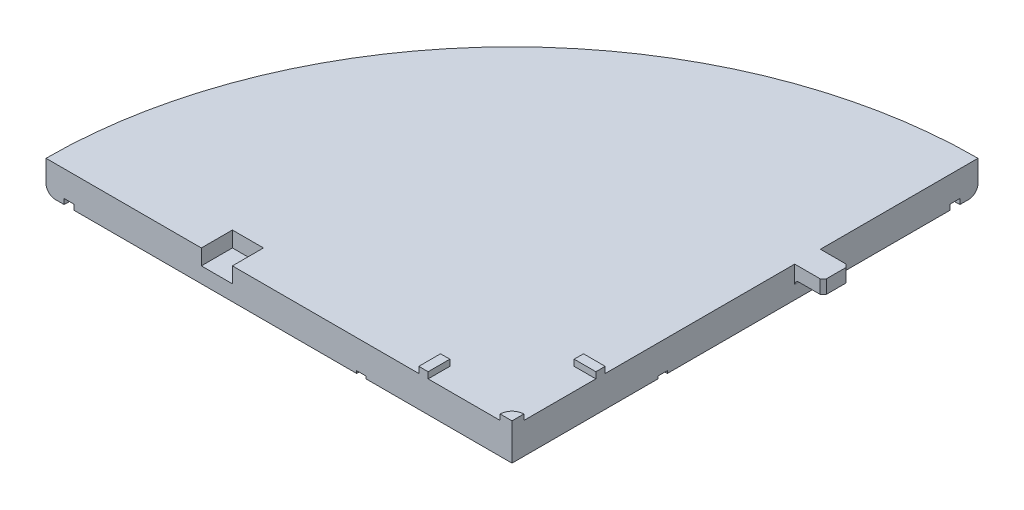
SolidWorks part; units mm, degrees
ref_plane "Front Plane" through (0, 0, 0) normal (0, 0, 1) x (1, 0, 0)
ref_plane "Top Plane" through (0, 0, 0) normal (0, 1, 0) x (1, 0, 0)
ref_plane "Right Plane" through (0, 0, 0) normal (1, 0, 0) x (0, 0, -1)
sketch "Sketch1" plane through (0, 0, 0) normal (0, 1, 0) x (1, 0, 0)
  circle A0 centre (0, 0) radius 150
extrude "Boss-Extrude3" add sketch "Sketch1" along normal blind 10
sketch "Sketch4" plane through (0, 10, 0) normal (0, 1, 0) x (1, 0, 0)
  line L0 (0, 0) -> (0, 162.3297)
  line L1 (0, 162.3297) -> (183.6782, 162.3297)
  line L2 (183.6782, 162.3297) -> (183.6782, -176.4278)
  line L3 (183.6782, -176.4278) -> (-217.9165, -176.4278)
  line L4 (-217.9165, -176.4278) -> (-217.9165, 0)
  line L5 (-217.9165, 0) -> (0, 0)
extrude "Cut-Extrude2" cut sketch "Sketch4" against normal blind 10
sketch "Sketch5" plane through (0, 10, 0) normal (0, 1, 0) x (1, 0, 0)
  line L0 (0, 3.825) -> (0, 0)
  line L1 (0, 0) -> (-3.825, 0)
  arc A0 (0, 3.825) -> (-3.825, 0) centre (0, 0) ccw
extrude "Boss-Extrude4" add sketch "Sketch5" along normal blind 1.8
sketch "Sketch6" plane through (0, 10, 0) normal (0, 1, 0) x (1, 0, 0)
  line L1 (-3.825, 0) -> (-150, 0) construction
  line L2 (-27, 0) -> (-27, 7)
  line L3 (-27, 7) -> (-30, 7)
  line L4 (-30, 7) -> (-30, 0)
  line L5 (-27, 0) -> (-30, 0)
extrude "Boss-Extrude5" add sketch "Sketch6" along normal blind 2
sketch "Sketch7" plane through (0, 10, 0) normal (0, 1, 0) x (1, 0, 0)
  line L1 (0, 150) -> (0, 3.825) construction
  line L2 (0, 27) -> (-7, 27)
  line L3 (-7, 27) -> (-7, 30)
  line L4 (-7, 30) -> (0, 30)
  line L5 (0, 30) -> (0, 27)
extrude "Boss-Extrude6" add sketch "Sketch7" along normal blind 2
sketch "Sketch8" plane through (0, 10, 0) normal (0, 1, 0) x (1, 0, 0)
  line L0 (0, 0) -> (-90, 0)
  line L1 (-30, 0) -> (-150, 0) construction
  line L2 (-90, 0) -> (-90, 10)
  line L3 (-90, 10) -> (-100, 10)
  line L4 (-100, 10) -> (-100, 0)
  line L5 (-100, 0) -> (-90, 0)
  line M8 (-150, 0) -> (-30, 0)
extrude "Cut-Extrude3" cut sketch "Sketch8" against normal blind 5 contours L3 L4 L2 M8
sketch "Sketch9" plane through (0, 10, 0) normal (0, 1, 0) x (1, 0, 0)
  line L0 (0, 0) -> (0, 91)
  line L1 (0, 150) -> (0, 30) construction
  line L2 (0, 91) -> (9.1938, 91)
  line L3 (9.1938, 91) -> (9.1938, 99.2773)
  line L4 (9.1938, 99.2773) -> (0, 99.2773)
  line L5 (0, 99.2773) -> (0, 91)
  line M13 (0, 30) -> (0, 150)
extrude "Boss-Extrude7" add sketch "Sketch9" against normal blind 4.35 contours L3 L4 L2 M13
chamfer "Chamfer1" distance 1 angle 45 2 edges at (9.1938, 7.825, -91) (9.1938, 7.825, -99.2773)
sketch "Sketch10" plane through (0, 0, 0) normal (0, -1, 0) x (1, 0, 0)
  line L0 (-140.9265, 0) -> (-144.1784, 0)
  line L1 (0, -140.9265) -> (0, -144.1784)
  arc A0 (-144.1784, 0) -> (0, -144.1784) centre (0, 0) ccw
  arc A1 (-140.9265, 0) -> (0, -140.9265) centre (0, 0) ccw
extrude "Cut-Extrude4" cut sketch "Sketch10" against normal blind 1.7
sketch "Sketch11" plane through (0, 0, 0) normal (0, -1, 0) x (-1, 0, 0)
  line L0 (47, 0) -> (50, 0)
  line L1 (47, 0) -> (50, 0)
  line L2 (0, 47) -> (0, 50)
  line L3 (0, 50) -> (50, 50)
  line L4 (50, 0) -> (50, 50)
  line L7 (0, 47) -> (47, 47)
  line L8 (47, 0) -> (47, 47)
  line L9 (0, 47) -> (0, 50)
extrude "Cut-Extrude5" cut sketch "Sketch11" against normal blind 0.8 contours L8 L3 L4 L7
fillet "Fillet1" radius 3 1 edges at (-106.066, 0, -106.066)
fillet "Fillet2" radius 1.4 1 edges at (0, 5.65, -95.1387)
